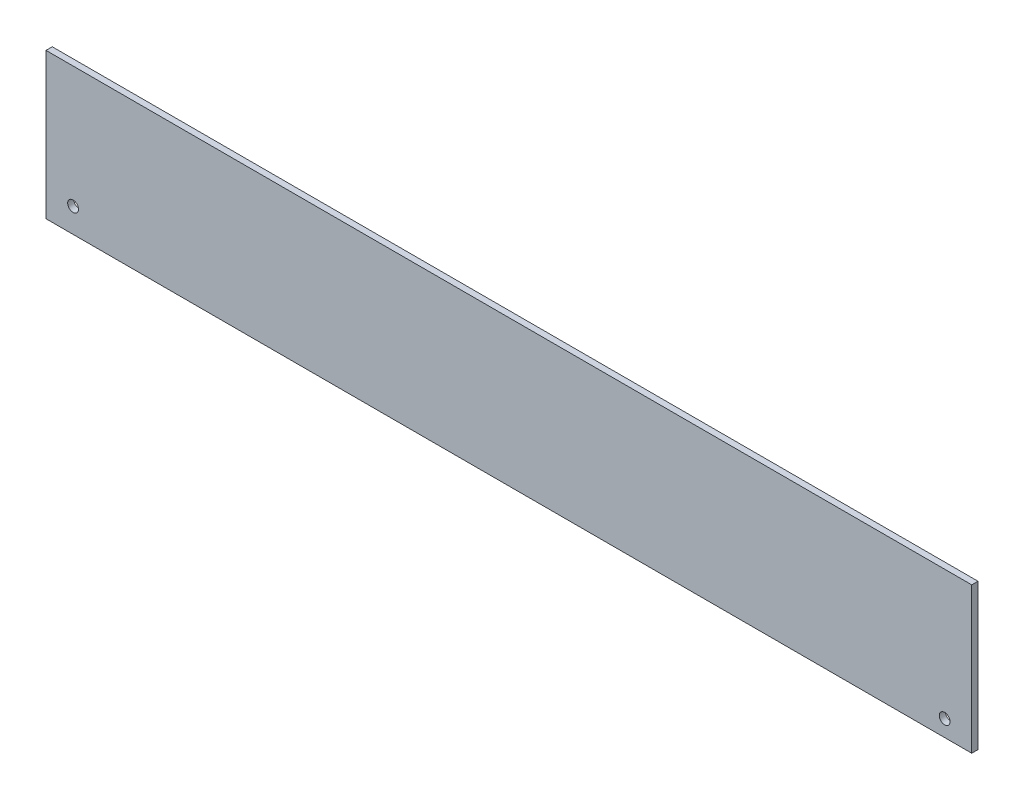
SolidWorks part; units mm, degrees
ref_plane "Plan de face" through (0, 0, 0) normal (0, 0, 1) x (1, 0, 0)
ref_plane "Plan de dessus" through (0, 0, 0) normal (0, 1, 0) x (1, 0, 0)
ref_plane "Plan de droite" through (0, 0, 0) normal (1, 0, 0) x (0, 0, -1)
sketch "Esquisse1" plane through (0, 0, 0) normal (0, 0, 1) x (1, 0, 0)
  line L1 (0, 0) -> (-444.3, 0)
  line L2 (0, 0) -> (0, 70)
  line L3 (0, 70) -> (-444.3, 70)
  line L4 (-444.3, 0) -> (-444.3, 70)
  dimension "D1" = 444.3
  dimension "D2" = 70
extrude "Boss.-Extru.1" add sketch "Esquisse1" along normal blind 3
sketch "Esquisse2" plane through (0, 0, 0) normal (0, 0, -1) x (-1, 0, 0)
  circle A4 centre (13, 7.8959) radius 2.6 construction
  circle A5 centre (431.3, 11.7217) radius 2.6 construction
  circle A6 centre (13, 7.8959) radius 2.6
  circle A7 centre (431.3, 11.7217) radius 2.6
extrude "Enlèv. mat.-Extru.1" cut sketch "Esquisse2" against normal blind 20
